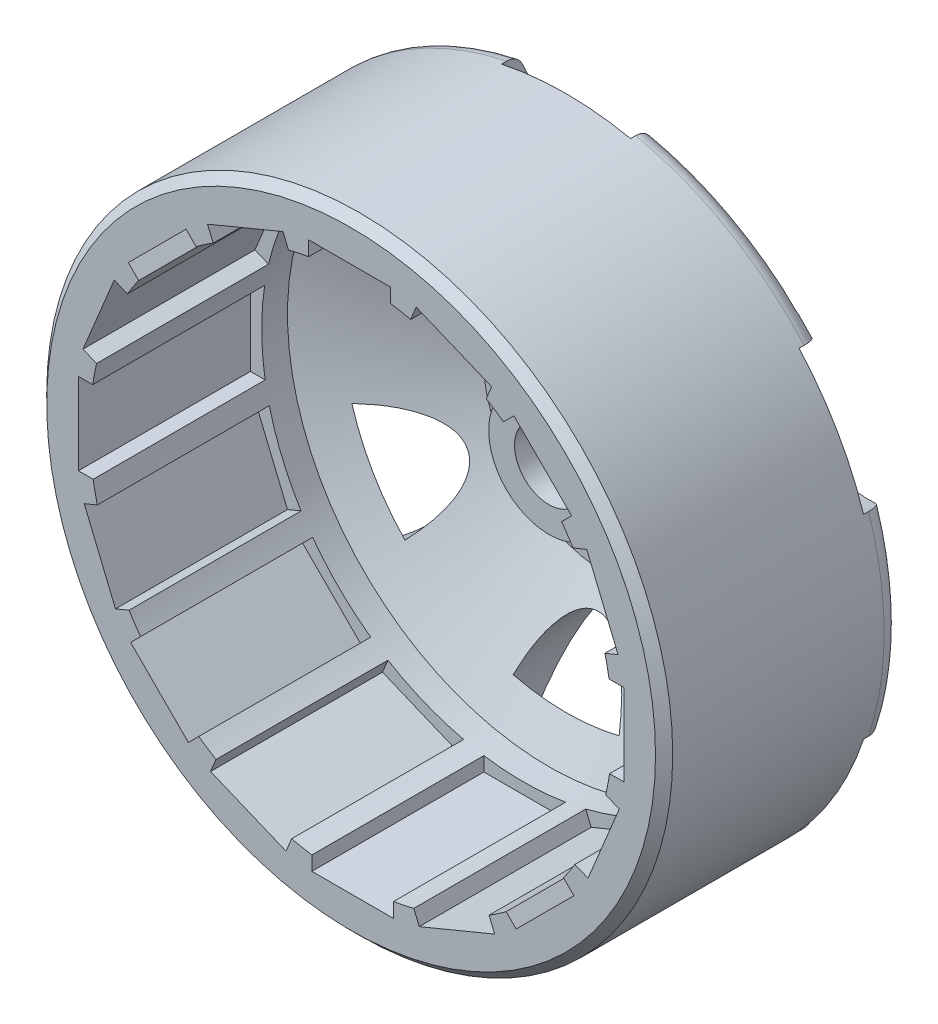
SolidWorks part; units mm, degrees
other "Markup1"
sketch "Sketch7" plane through (36.4, 36.4, 23) normal (0.0117, 0.9999, 0.0073) x (0.5301, 0, -0.8479)
ref_plane "Front Plane" through (0, 0, 0) normal (0, 0, 1) x (1, 0, 0)
ref_plane "Top Plane" through (0, 0, 0) normal (0, 1, 0) x (1, 0, 0)
ref_plane "Right Plane" through (0, 0, 0) normal (1, 0, 0) x (0, 0, -1)
sketch "Sketch1" plane through (0, 0, 0) normal (0, 1, 0) x (1, 0, 0)
  line L1 (0, 14.5) -> (-7, 14.5)
  line L2 (-7, 14.5) -> (-7, 12)
  line L3 (-7, 12) -> (-18.32, 12)
  line L4 (-18.32, 12) -> (-35.2191, 4.4134)
  line L5 (-36.4, 2.5889) -> (-36.4, -22)
  line L6 (-35.4, -23) -> (-30.4, -23)
  line L8 (-30.4, 0) -> (-14.7, 7.0482)
  line L9 (-14.7, 7.0482) -> (-10.65, 7.0482)
  line L11 (-7, 0) -> (0, 0)
  line L12 (0, 0) -> (0, 14.5)
  line L17 (-36.4, -22) -> (-35.4, -23)
  line L23 (-10.65, 7.0482) -> (-7, 0)
  line L25 (-30.4, 0) -> (-30.4, -23)
  arc A0 (-35.2191, 4.4134) -> (-36.4, 2.5889) centre (-34.4, 2.5889) ccw
  point P8 (-36.4, -23)
  dimension "D13" = 2
  dimension "D1" = 7
  dimension "D2" = 23
  dimension "D4" = 6
  dimension "D5" = 30.4
  dimension "D6" = 2.5
  dimension "D7" = 6
  dimension "D3" = 23
  dimension "D8" = 37.5
  dimension "D9" = 14.7
  dimension "D10" = 18.32
  dimension "D11" = 7.0482
  dimension "D12" = 10.65
revolve "Revolve1" add sketch "Sketch1" angle 360 about L12
sketch "Sketch3" plane through (0, 0, 0) normal (0, 0, 1) x (1, 0, 0)
  circle A0 centre (0, 0) radius 4
  dimension "D1" = 8
extrude "Cut-Extrude2" cut sketch "Sketch3" against normal blind 20
sketch "Sketch4" plane through (0, 0, -12) normal (0, 0, -1) x (-1, 0, 0)
  line L0 (0, 0) -> (0, 35.2191) construction
  circle A0 centre (0, 0) radius 35.2191 construction
  ellipse E0 centre (0, 35.2191) end of major axis (0, 17.6096) minor radius 7.5
  ellipse E1 centre (30.5006, 17.6096) end of major axis (15.2503, 8.8048) minor radius 7.5
  ellipse E2 centre (30.5006, -17.6096) end of major axis (15.2503, -8.8048) minor radius 7.5
  ellipse E3 centre (0, -35.2191) end of major axis (0, -17.6096) minor radius 7.5
  ellipse E4 centre (-30.5006, -17.6096) end of major axis (-15.2503, -8.8048) minor radius 7.5
  ellipse E5 centre (-30.5006, 17.6096) end of major axis (-15.2503, 8.8048) minor radius 7.5
  point P32 (0, 0)
  dimension "D1" = 15
  dimension "D2" = 6
extrude "Cut-Extrude4" cut sketch "Sketch4" against normal blind 10
sketch "Sketch6" plane through (0, 0, 23) normal (0, 0, 1) x (1, 0, 0)
  line L0 (0, 30.4) -> (0, 35.4) construction
  line L1 (7.5704, 31.1824) -> (6.9161, 29.6028)
  line L2 (-4.9389, 31.7059) -> (4.5611, 31.7059)
  line L3 (-4.9389, 31.7059) -> (-4.9389, 29.9961)
  line L5 (4.5611, 31.7059) -> (4.5611, 30.0559)
  line L6 (-4.9389, 31.7059) -> (0, 30.4) construction
  line L7 (0, 30.4) -> (4.5611, 31.7059) construction
  line L8 (7.5704, 31.1824) -> (16.3472, 27.547)
  line L9 (16.3472, 27.547) -> (15.7158, 26.0225)
  line L10 (18.9271, 25.9118) -> (17.7182, 24.7028)
  line L11 (18.9271, 25.9118) -> (25.6446, 19.1942)
  line L12 (25.6446, 19.1942) -> (24.4779, 18.0275)
  line L13 (27.4024, 16.6962) -> (25.8228, 16.0419)
  line L14 (27.4024, 16.6962) -> (31.0379, 7.9194)
  line L15 (31.0379, 7.9194) -> (29.5135, 7.288)
  line L16 (31.7059, 4.9389) -> (29.9961, 4.9389)
  line L17 (31.7059, 4.9389) -> (31.7059, -4.5611)
  line L18 (31.7059, -4.5611) -> (30.0559, -4.5611)
  line L19 (31.1824, -7.5704) -> (29.6028, -6.9161)
  line L20 (31.1824, -7.5704) -> (27.547, -16.3472)
  line L21 (27.547, -16.3472) -> (26.0225, -15.7158)
  line L22 (25.9118, -18.9271) -> (24.7028, -17.7182)
  line L23 (25.9118, -18.9271) -> (19.1942, -25.6446)
  line L24 (19.1942, -25.6446) -> (18.0275, -24.4779)
  line L25 (16.6962, -27.4024) -> (16.0419, -25.8228)
  line L26 (16.6962, -27.4024) -> (7.9194, -31.0379)
  line L27 (7.9194, -31.0379) -> (7.288, -29.5135)
  line L28 (4.9389, -31.7059) -> (4.9389, -29.9961)
  line L29 (4.9389, -31.7059) -> (-4.5611, -31.7059)
  line L30 (-4.5611, -31.7059) -> (-4.5611, -30.0559)
  line L31 (-7.5704, -31.1824) -> (-6.9161, -29.6028)
  line L32 (-7.5704, -31.1824) -> (-16.3472, -27.547)
  line L33 (-16.3472, -27.547) -> (-15.7158, -26.0225)
  line L34 (-18.9271, -25.9118) -> (-17.7182, -24.7028)
  line L35 (-18.9271, -25.9118) -> (-25.6446, -19.1942)
  line L36 (-25.6446, -19.1942) -> (-24.4779, -18.0275)
  line L37 (-27.4024, -16.6962) -> (-25.8228, -16.0419)
  line L38 (-27.4024, -16.6962) -> (-31.0379, -7.9194)
  line L39 (-31.0379, -7.9194) -> (-29.5135, -7.288)
  line L40 (-31.7059, -4.9389) -> (-29.9961, -4.9389)
  line L41 (-31.7059, -4.9389) -> (-31.7059, 4.5611)
  line L42 (-31.7059, 4.5611) -> (-30.0559, 4.5611)
  line L43 (-31.1824, 7.5704) -> (-29.6028, 6.9161)
  line L44 (-31.1824, 7.5704) -> (-27.547, 16.3472)
  line L45 (-27.547, 16.3472) -> (-26.0225, 15.7158)
  line L46 (-25.9118, 18.9271) -> (-24.7028, 17.7182)
  line L47 (-25.9118, 18.9271) -> (-19.1942, 25.6446)
  line L48 (-19.1942, 25.6446) -> (-18.0275, 24.4779)
  line L49 (-16.6962, 27.4024) -> (-16.0419, 25.8228)
  line L50 (-16.6962, 27.4024) -> (-7.9194, 31.0379)
  line L51 (-7.9194, 31.0379) -> (-7.288, 29.5135)
  arc A0 (4.5611, 30.0559) -> (-4.9389, 29.9961) centre (0, 0) ccw
  circle A1 centre (0, 0) radius 35.4 construction
  circle A3 centre (0, 0) radius 30.4 construction
  arc A4 (15.7158, 26.0225) -> (6.9161, 29.6028) centre (0, 0) ccw
  arc A5 (24.4779, 18.0275) -> (17.7182, 24.7028) centre (0, 0) ccw
  arc A6 (29.5135, 7.288) -> (25.8228, 16.0419) centre (0, 0) ccw
  arc A7 (30.0559, -4.5611) -> (29.9961, 4.9389) centre (0, 0) ccw
  arc A8 (26.0225, -15.7158) -> (29.6028, -6.9161) centre (0, 0) ccw
  arc A9 (18.0275, -24.4779) -> (24.7028, -17.7182) centre (0, 0) ccw
  arc A10 (7.288, -29.5135) -> (16.0419, -25.8228) centre (0, 0) ccw
  arc A11 (-4.5611, -30.0559) -> (4.9389, -29.9961) centre (0, 0) ccw
  arc A12 (-15.7158, -26.0225) -> (-6.9161, -29.6028) centre (0, 0) ccw
  arc A13 (-24.4779, -18.0275) -> (-17.7182, -24.7028) centre (0, 0) ccw
  arc A14 (-29.5135, -7.288) -> (-25.8228, -16.0419) centre (0, 0) ccw
  arc A15 (-30.0559, 4.5611) -> (-29.9961, -4.9389) centre (0, 0) ccw
  arc A16 (-26.0225, 15.7158) -> (-29.6028, 6.9161) centre (0, 0) ccw
  arc A17 (-18.0275, 24.4779) -> (-24.7028, 17.7182) centre (0, 0) ccw
  arc A18 (-7.288, 29.5135) -> (-16.0419, 25.8228) centre (0, 0) ccw
  point P84 (0, 0)
  dimension "D1" = 9.5
  dimension "D2" = 1.65
  dimension "D3" = 4.5611
  dimension "D4" = 16
extrude "Cut-Extrude5" cut sketch "Sketch6" against normal blind 20
equation "\"shaft dia\"=8"
equation "\"magnet length\"= 20mm"
equation "\"rotor side thickness\"=6"
equation "\"rotor inner dia\"= 30.4"
equation "\"D5@Sketch1\"=\"rotor inner dia\""
equation "\"D1@Sketch3\"= \"shaft dia\""
equation "\"D4@Sketch1\"=\"rotor side thickness\""
equation "\"D7@Sketch1\"=\"rotor side thickness\""
equation "\"D10@Sketch1\"=\"rotor inner dia\"-12.08"
equation "\"D9@Sketch1\"=\"rotor inner dia\"-15.7"
equation "\"D1@Cut-Extrude5\"=\"magnet length\""
